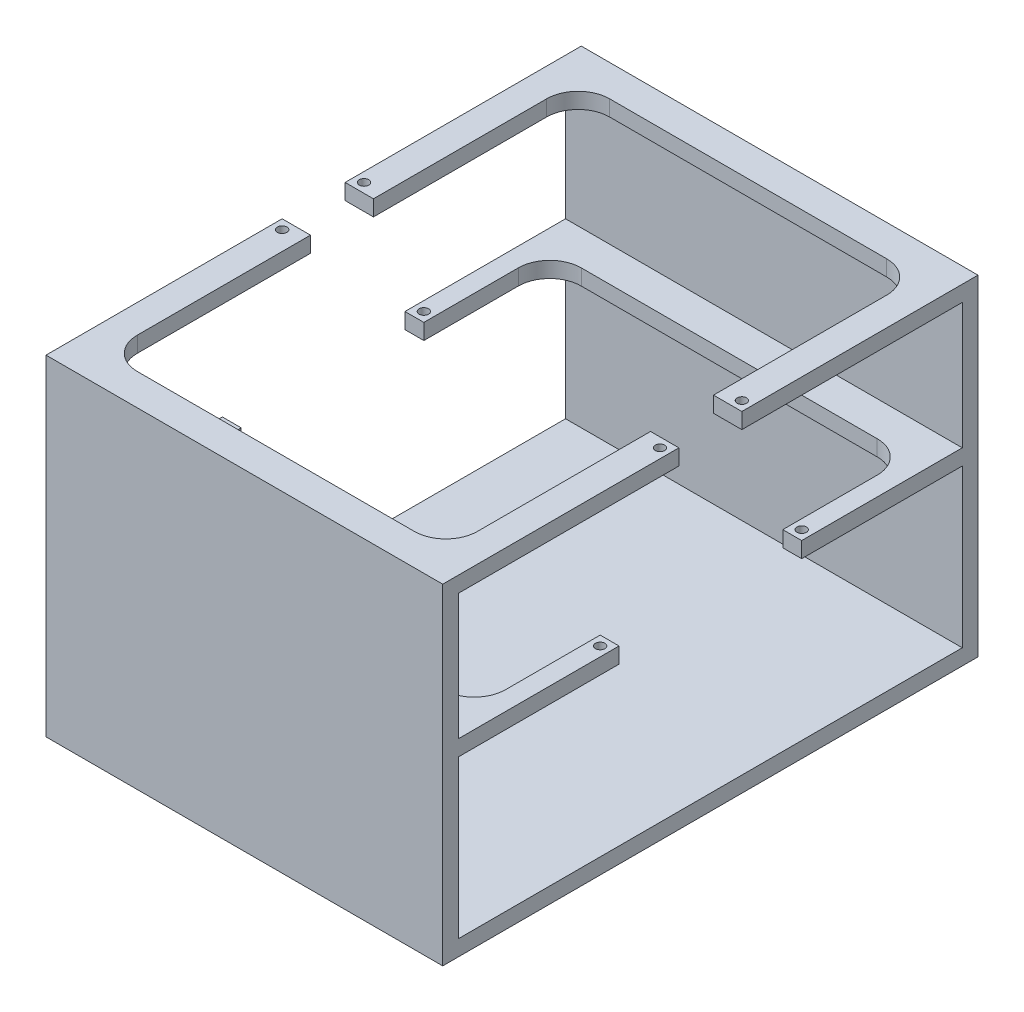
SolidWorks part; units mm, degrees
ref_plane "Front Plane" through (0, 0, 0) normal (0, 0, 1) x (1, 0, 0)
ref_plane "Top Plane" through (0, 0, 0) normal (0, 1, 0) x (1, 0, 0)
ref_plane "Right Plane" through (0, 0, 0) normal (1, 0, 0) x (0, 0, -1)
sketch "Sketch1" plane through (0, 0, 0) normal (1, 0, 0) x (0, 0, -1)
  line L0 (-95, 46.4295) -> (-95, -3.5705)
  line L1 (-25, 91.4295) -> (-95, 91.4295)
  line L2 (-25, 91.4295) -> (-25, 96.4295)
  line L3 (-25, 96.4295) -> (-100, 96.4295)
  line L4 (-100, 86.4295) -> (-100, 96.4295)
  line L5 (-100, 96.4295) -> (-90, 96.4295)
  line L6 (-100, 96.4295) -> (-100, -8.5705)
  line L7 (-100, -8.5705) -> (-90, -8.5705)
  line L8 (-95, 91.4295) -> (-95, 51.4295)
  line L9 (-95, 51.4295) -> (-44, 51.4295)
  line L11 (-95, 46.4295) -> (-44, 46.4295)
  line L12 (-44, 51.4295) -> (-44, 46.4295)
  line L13 (-90, -8.5705) -> (-15, -8.5705)
  line L15 (-95, -3.5705) -> (-15, -3.5705)
  line L16 (-15, -8.5705) -> (-15, -3.5705)
  dimension "D1" = 5
  dimension "D2" = 75
  dimension "D3" = 5
  dimension "D4" = 105
  dimension "D5" = 55
  dimension "D6" = 5
  dimension "D7" = 19
  dimension "D8" = 5
  dimension "D9" = 85
extrude "Boss-Extrude1" add sketch "Sketch1" along normal blind 126 contours L13 L16 L15 L0 L11 L12 L9 L8 L1 L2 L3 L4 L6 L7
sketch "Sketch2" plane through (0, 96.4295, 0) normal (0, 1, 0) x (1, 0, 0)
  line L0 (0, -55) -> (0, 55) construction
  line L2 (126, -25) -> (0, -25) construction
  circle A0 centre (3, -28) radius 1.5
  circle A1 centre (123, -28) radius 1.5
  dimension "D1" = 3
  dimension "D2" = 3
  dimension "D3" = 120
  dimension "D4" = 3
  dimension "D5" = 3
extrude "Cut-Extrude1" cut sketch "Sketch2" against normal up to surface (45 mm away) contours A1 | A0 up to face at (63, 51.4295, 69.5)
sketch "Sketch3" plane through (0, 51.4295, 0) normal (0, 1, 0) x (1, 0, 0)
  line L0 (0, -95) -> (0, -44) construction
  line L1 (126, -95) -> (126, -44) construction
  line L7 (6, -95) -> (6, -44)
  line L8 (6, -74) -> (6, -44)
  line L9 (16, -84) -> (110, -84)
  line L10 (120, -95) -> (120, -44)
  line L11 (120, -74) -> (120, -44)
  line L12 (6, -44) -> (120, -44)
  circle A0 centre (3, -47) radius 1.5
  circle A1 centre (123, -47) radius 1.5
  circle A2 centre (123, -28) radius 1.5 construction
  arc A3 (16, -84) -> (6, -74) centre (16, -74) cw
  arc A4 (110, -84) -> (120, -74) centre (110, -74) ccw
  dimension "D1" = 3
  dimension "D2" = 3
  dimension "D4" = 3
  dimension "D5" = 19
  dimension "D8" = 10
  dimension "D9" = 10
  dimension "D3" = 3
  dimension "D6" = 6
  dimension "D10" = 40
  dimension "D7" = 6
extrude "Cut-Extrude3" cut sketch "Sketch3" against normal up to surface (55 mm away) contours A0 | A1 | L11 L12 L8 A3 L9 A4 up to face at (63, -3.5705, 55)
ref_plane "Plane1" through (0, 0, 15) normal (0, 0, -1) x (-1, 0, 0)
mirror "Mirror2" about plane through (0, 0, 15) normal (0, 0, -1) of "Cut-Extrude1", "Cut-Extrude3", "Boss-Extrude1"
sketch "Sketch4" plane through (0, 96.4295, 0) normal (0, 1, 0) x (1, 0, 0)
  line L0 (9, -25) -> (9, -80)
  line L1 (126, -25) -> (0, -25) construction
  line L2 (19, -90) -> (107, -90)
  line L3 (117, -80) -> (117, -25)
  line L4 (9, -25) -> (117, -25)
  line L6 (9, -25) -> (117, -25)
  circle A0 centre (3, -28) radius 1.5 construction
  circle A1 centre (123, -28) radius 1.5 construction
  arc A2 (107, -90) -> (117, -80) centre (107, -80) ccw
  arc A3 (19, -90) -> (9, -80) centre (19, -80) cw
  dimension "D1" = 6
  dimension "D4" = 10
  dimension "D2" = 6
  dimension "D3" = 65
extrude "Cut-Extrude6" cut sketch "Sketch4" against normal up to surface (45 mm away) contours L4 L3 A2 L2 A3 L0 up to face at (3, 51.4295, 48.5)
mirror "Mirror5" about plane through (0, 0, 15) normal (0, 0, -1) of "Cut-Extrude6"
